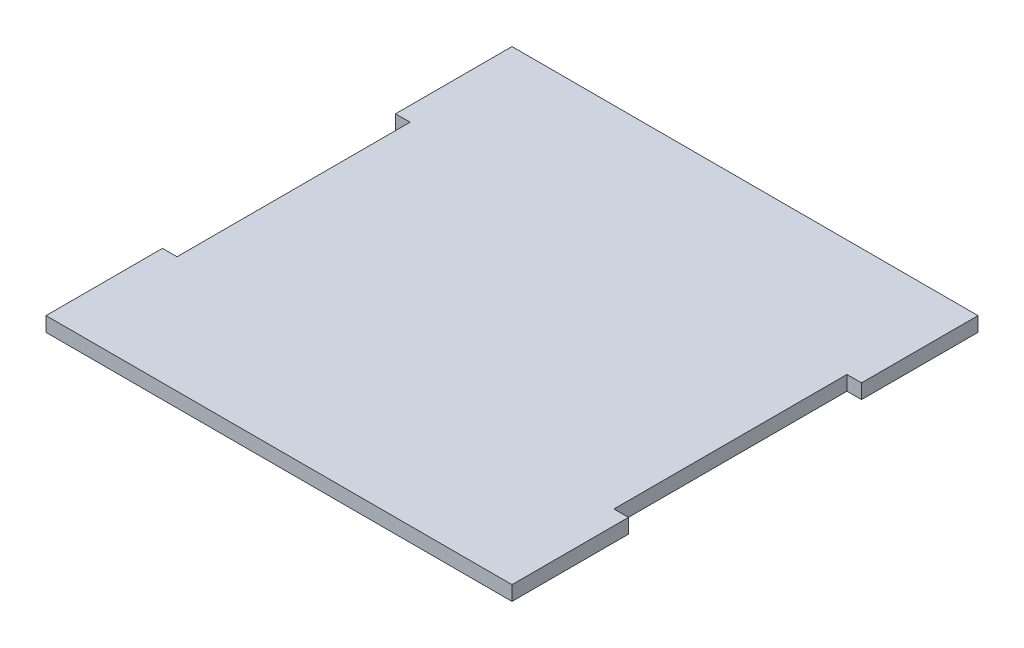
SolidWorks part; units mm, degrees
ref_plane "Front Plane" through (0, 0, 0) normal (0, 0, 1) x (1, 0, 0)
ref_plane "Top Plane" through (0, 0, 0) normal (0, 1, 0) x (1, 0, 0)
ref_plane "Right Plane" through (0, 0, 0) normal (1, 0, 0) x (0, 0, -1)
sketch "Sketch1" plane through (0, 0, 0) normal (0, 1, 0) x (1, 0, 0)
  line L0 (101.6, 0) -> (0, 0)
  line L2 (0, 0) -> (0, 101.6)
  line L3 (0, 101.6) -> (101.6, 101.6)
  line L4 (101.6, 0) -> (101.6, 101.6)
  line L5 (0, 25.4) -> (3.175, 25.4)
  line L6 (0, 25.4) -> (0, 76.2)
  line L7 (0, 76.2) -> (3.175, 76.2)
  line L8 (3.175, 25.4) -> (3.175, 76.2)
  line L14 (101.6, 25.4) -> (98.425, 25.4)
  line L15 (98.425, 25.4) -> (98.425, 76.2)
  line L16 (101.6, 76.2) -> (98.425, 76.2)
extrude "Boss-Extrude1" add sketch "Sketch1" along normal blind 3.175
